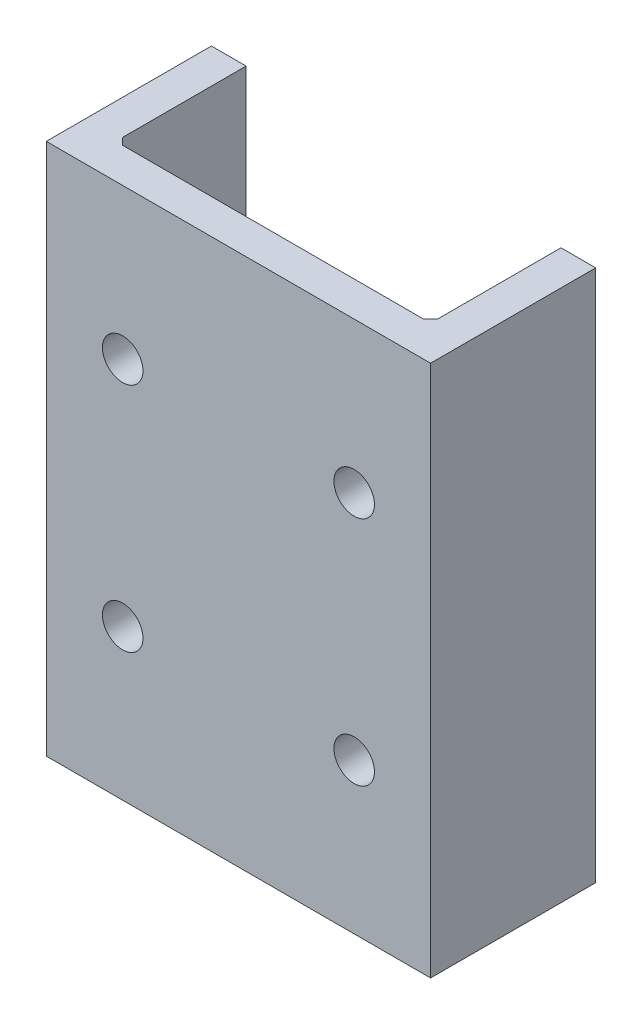
SolidWorks part; units mm, degrees
ref_plane "Plan de face" through (0, 0, 0) normal (0, 0, 1) x (1, 0, 0)
ref_plane "Plan de dessus" through (0, 0, 0) normal (0, 1, 0) x (1, 0, 0)
ref_plane "Plan de droite" through (0, 0, 0) normal (1, 0, 0) x (0, 0, -1)
sketch "Esquisse1" plane through (0, 0, 0) normal (0, 1, 0) x (1, 0, 0)
  line L4 (-13.6, 11.266) -> (-13.6, 0.6)
  line L5 (-13.6, 0.6) -> (-13, 0)
  line L6 (-13, 0) -> (13, 0)
  line L7 (13, 0) -> (13.6, 0.6)
  line L8 (13.6, 0.6) -> (13.6, 11.266)
  line L9 (-13.6, 11.266) -> (-16.6, 11.266)
  line L10 (-16.6, 11.266) -> (-16.6, -3)
  line L11 (-16.6, -3) -> (16.6, -3)
  line L12 (16.6, -3) -> (16.6, 11.266)
  line L13 (16.6, 11.266) -> (13.6, 11.266)
  point P2 (0, 0)
  dimension "D1" = 27.2
  dimension "D2" = 0.6
  dimension "D3" = 0.6
  dimension "D4" = 3
  dimension "D5" = 3
extrude "Boss.-Extru.1" add sketch "Esquisse1" along normal blind 46
sketch "Esquisse2" plane through (0, 0, 3) normal (0, 0, 1) x (1, 0, 0)
  line L0 (0, 23) -> (0, 0) construction
  line L1 (-10, 13) -> (10, 13) construction
  line L2 (-10, 13) -> (-10, 33) construction
  line L3 (-10, 33) -> (10, 33) construction
  line L4 (10, 13) -> (10, 33) construction
  line L5 (-10, 13) -> (10, 33) construction
  line L6 (-10, 33) -> (10, 13) construction
  line L7 (0, 23) -> (-16.6, 23) construction
  line L8 (-16.6, 46) -> (-16.6, 0) construction
  circle A0 centre (-10, 33) radius 1.75
  circle A1 centre (10, 33) radius 1.75
  circle A2 centre (10, 13) radius 1.75
  circle A3 centre (-10, 13) radius 1.75
  point P0 (0, 23)
  dimension "D1" = 3.5
  dimension "D2" = 20
extrude "Enlèv. mat.-Extru.1" cut sketch "Esquisse2" against normal up to next
